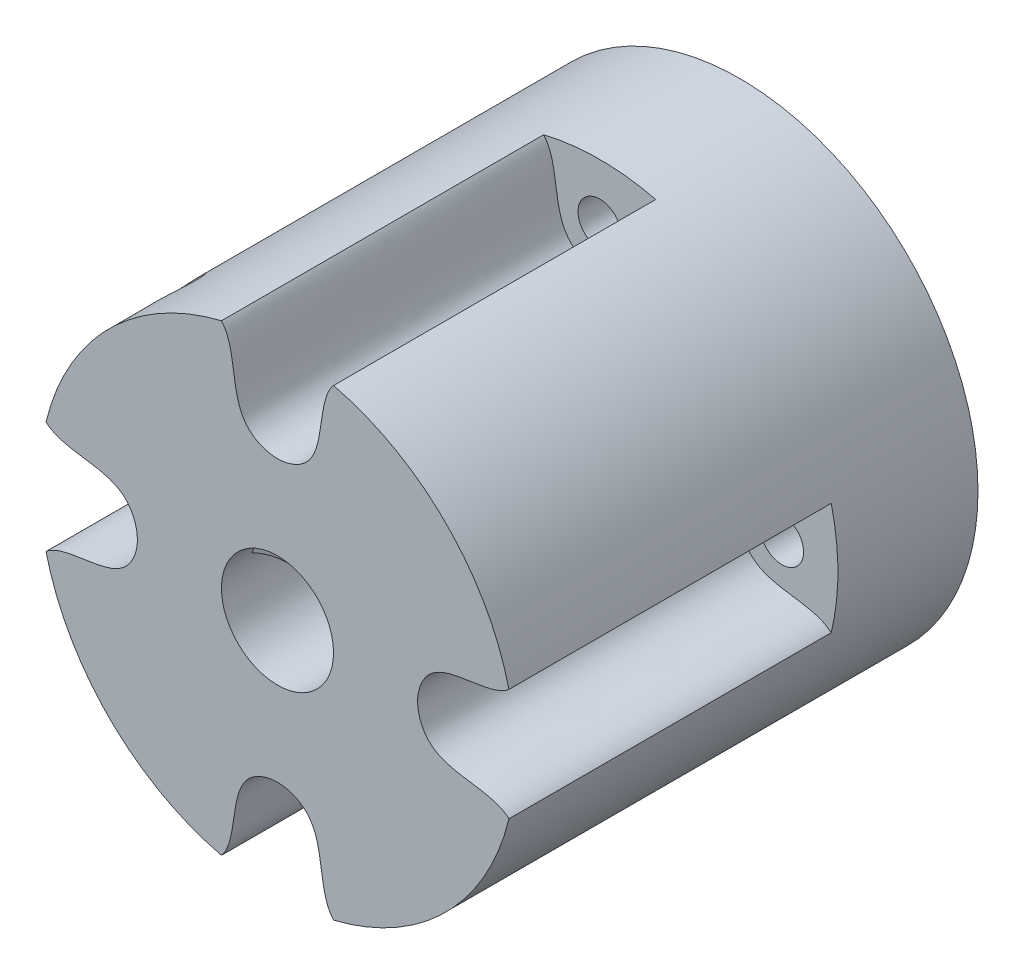
SolidWorks part; units mm, degrees
ref_plane "Front Plane" through (0, 0, 0) normal (0, 0, 1) x (1, 0, 0)
ref_plane "Top Plane" through (0, 0, 0) normal (0, 1, 0) x (1, 0, 0)
ref_plane "Right Plane" through (0, 0, 0) normal (1, 0, 0) x (0, 0, -1)
sketch "Sketch1" plane through (0, 0, 0) normal (0, 0, 1) x (1, 0, 0)
  circle A0 centre (0, 0) radius 17
  dimension "D1" = 34
extrude "Boss-Extrude1" add sketch "Sketch1" along normal blind 10
sketch "Sketch2" plane through (0, 0, 10) normal (0, 0, 1) x (1, 0, 0)
  line L0 (-22.4944, 0) -> (20.7855, 0) construction
  circle A0 centre (0, 0) radius 13 construction
  circle A1 centre (13, 0) radius 1.55
  circle A2 centre (0, -13) radius 1.55
  circle A3 centre (-13, 0) radius 1.55
  circle A4 centre (0, 13) radius 1.55
  point P16 (0, 0)
  dimension "D1" = 26
  dimension "D2" = 3.1
  dimension "D3" = 4
extrude "Cut-Extrude1" cut sketch "Sketch2" against normal through all
sketch "Sketch3" plane through (0, 0, 10) normal (0, 0, 1) x (1, 0, 0)
  line L0 (0, -18.0035) -> (0, 17.5663) construction
  line L1 (-17.924, 0) -> (18.5201, 0) construction
  line L2 (0, 13) -> (3, 10) construction
  line L3 (0, 13) -> (-3.406, 9.594) construction
  circle A0 centre (0, 0) radius 9.5 construction
  arc A1 (16.5227, 4) -> (4, 16.5227) centre (0, 0) ccw
  circle A2 centre (0, 13) radius 3 construction
  circle A3 centre (0, 0) radius 17 construction
  arc A4 (4, -16.5227) -> (16.5227, -4) centre (0, 0) ccw
  arc A5 (-16.5227, -4) -> (-4, -16.5227) centre (0, 0) ccw
  arc A6 (-4, 16.5227) -> (-16.5227, 4) centre (0, 0) ccw
  spline S0 degree 3 poles (4, 16.5227) (2.8162, 15.1791) (3.696, 11.19) (0, 9.669) (-3.696, 11.19) (-2.8162, 15.1791) (-4, 16.5227) knots 0 0 0 0 0.360911 0.5 0.639089 1 1 1 1
  spline S1 degree 3 poles (16.5227, -4) (15.1791, -2.8162) (11.19, -3.696) (9.669, 0) (11.19, 3.696) (15.1791, 2.8162) (16.5227, 4) knots 0 0 0 0 0.360911 0.5 0.639089 1 1 1 1
  spline S2 degree 3 poles (-4, -16.5227) (-2.8162, -15.1791) (-3.696, -11.19) (0, -9.669) (3.696, -11.19) (2.8162, -15.1791) (4, -16.5227) knots 0 0 0 0 0.360911 0.5 0.639089 1 1 1 1
  spline S3 degree 3 poles (-16.5227, 4) (-15.1791, 2.8162) (-11.19, 3.696) (-9.669, 0) (-11.19, -3.696) (-15.1791, -2.8162) (-16.5227, -4) knots 0 0 0 0 0.360911 0.5 0.639089 1 1 1 1
  point P4 (4, 16.5227)
  point P5 (-4, 16.5227)
  point P45 (0, 0)
  point P48 (0, 0)
  dimension "D1" = 19
  dimension "D2" = 6
  dimension "D3" = 4
extrude "Boss-Extrude3" add sketch "Sketch3" along normal blind 23
sketch "Sketch4" plane through (0, 0, 33) normal (0, 0, 1) x (1, 0, 0)
  circle A0 centre (0, 0) radius 4
  dimension "D1" = 8
extrude "Cut-Extrude2" cut sketch "Sketch4" against normal blind 23
ref_plane "Plane1" through (-12.0208, 12.0208, 0) normal (-0.7071, 0.7071, 0) x (0, 0, -1)
sketch "Sketch7" plane through (-12.0208, 12.0208, 0) normal (-0.7071, 0.7071, 0) x (0, 0, -1)
  line L0 (-36.2133, 0) -> (5.8112, 0) construction
  line L1 (-33, 8.8549) -> (-33, -8.8549) construction
  circle A0 centre (-28, 0) radius 1.55
  dimension "D1" = 3.1
  dimension "D2" = 5
extrude "Cut-Extrude3" cut sketch "Sketch7" against normal blind 15
ref_plane "Plane2" through (0, 0, 0) normal (-0.7071, 0.7071, 0) x (0, 0, -1)
sketch "Sketch11" plane through (0, 0, 0) normal (-0.7071, 0.7071, 0) x (0, 0, -1)
  line L1 (-28, 3.5) -> (-31.0311, 1.75)
  line L2 (-31.0311, 1.75) -> (-31.0311, -1.75)
  line L3 (-31.0311, -1.75) -> (-28, -3.5)
  line L4 (-28, -3.5) -> (-24.9689, -1.75)
  line L5 (-24.9689, -1.75) -> (-24.9689, 1.75)
  line L6 (-24.9689, 1.75) -> (-28, 3.5)
  circle A0 centre (-28, 0) radius 3.0311 construction
  dimension "D1" = 3.5
extrude "Cut-Extrude6" cut sketch "Sketch11" along normal blind 7
